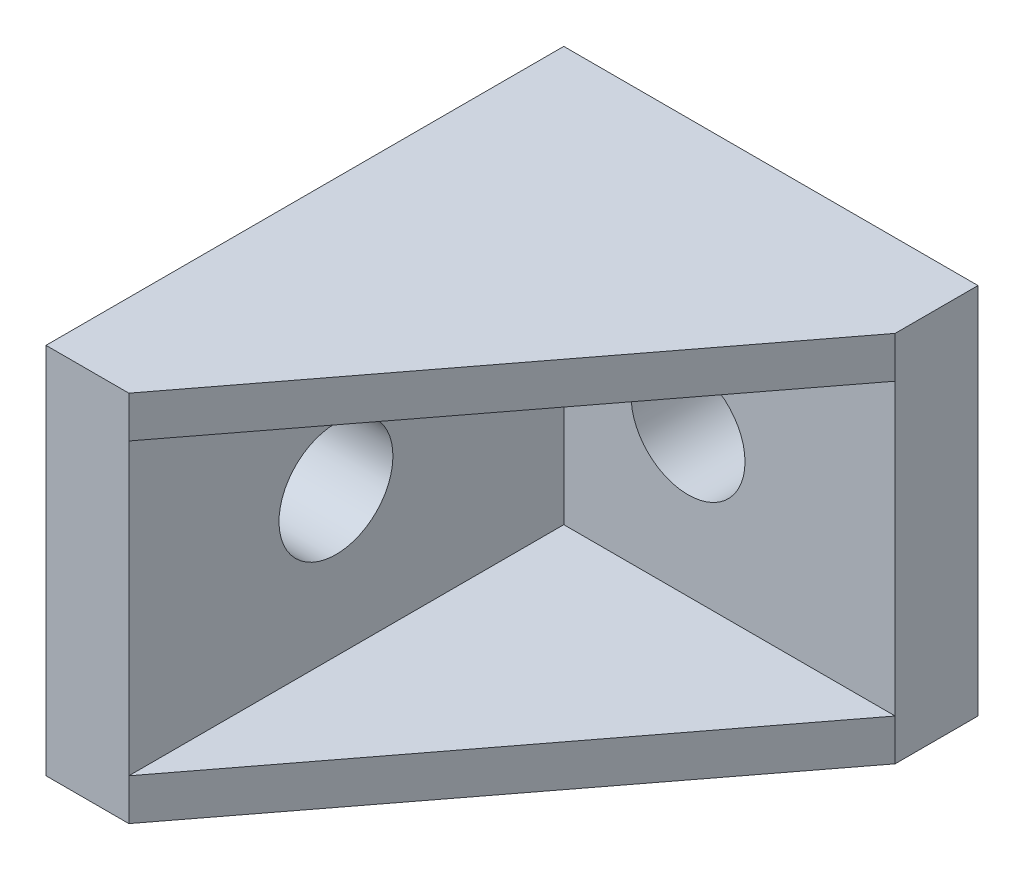
SolidWorks part; units mm, degrees
ref_plane "정면" through (0, 0, 0) normal (0, 0, 1) x (1, 0, 0)
ref_plane "윗면" through (0, 0, 0) normal (0, 1, 0) x (1, 0, 0)
ref_plane "우측면" through (0, 0, 0) normal (1, 0, 0) x (0, 0, -1)
sketch "스케치1" plane through (0, 0, 0) normal (0, 0, 1) x (1, 0, 0)
  line L1 (-10, 9) -> (10, 9)
  line L2 (-10, 9) -> (-10, -9)
  line L3 (-10, -9) -> (10, -9)
  line L4 (10, 9) -> (10, -9)
  line L5 (-10, 9) -> (10, -9) construction
  line L6 (-10, -9) -> (10, 9) construction
  point P0 (0, 0)
  dimension "D1" = 20
  dimension "D2" = 18
extrude "보스-돌출1" add sketch "스케치1" along normal blind 25
sketch "스케치2" plane through (0, 0, 25) normal (0, 0, 1) x (1, 0, 0)
  line L0 (10, -9) -> (10, 9) construction
  line L1 (10, 7) -> (-6, 7)
  line L2 (10, 7) -> (10, -7)
  line L3 (10, -7) -> (-6, -7)
  line L4 (-6, 7) -> (-6, -7)
  line L5 (-10, 9) -> (-10, -9) construction
  line L6 (10, 9) -> (-10, 9) construction
  line L7 (-10, -9) -> (10, -9) construction
  point P10 (0, 9)
  dimension "D1" = 4
  dimension "D2" = 2
  dimension "D3" = 2
extrude "컷-돌출1" cut sketch "스케치2" against normal blind 21
sketch "스케치4" plane through (0, -7, 0) normal (0, 1, 0) x (1, 0, 0)
  line L0 (-6, -25) -> (10, -4)
  line L1 (10, -4) -> (10, -25)
  line L2 (10, -25) -> (-6, -25)
extrude "컷-돌출2" cut sketch "스케치4" against normal through all both and the other way through all
sketch "스케치5" plane through (0, 0, 4) normal (0, 0, 1) x (1, 0, 0)
  line L0 (10, 7) -> (-6, 7) construction
  line L5 (-10, 9) -> (-10, -9) construction
  circle A2 centre (0, 0) radius 2.75
  dimension "D2" = 7
  dimension "D1" = 5.5
  dimension "D3" = 10
extrude "컷-돌출3" cut sketch "스케치5" against normal through all both
sketch "스케치6" plane through (-6, 0, 0) normal (1, 0, 0) x (0, 0, -1)
  line L0 (-4, 7) -> (-25, 7) construction
  line L5 (-25, 7) -> (-25, -7) construction
  circle A2 centre (-15, 0) radius 2.75
  dimension "D2" = 7
  dimension "D1" = 5.5
  dimension "D3" = 10
extrude "컷-돌출4" cut sketch "스케치6" against normal through all both
